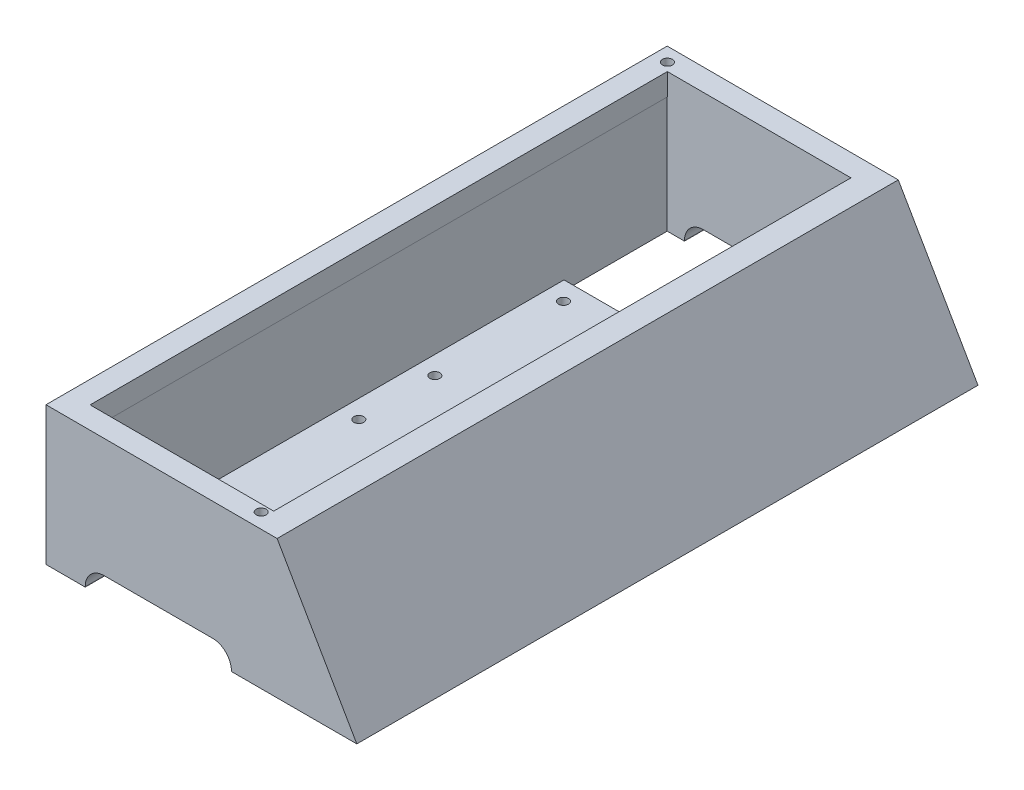
SolidWorks part; units mm, degrees
ref_plane "Alzado" through (0, 0, 0) normal (0, 0, 1) x (1, 0, 0)
ref_plane "Planta" through (0, 0, 0) normal (0, 1, 0) x (1, 0, 0)
ref_plane "Vista lateral" through (0, 0, 0) normal (1, 0, 0) x (0, 0, -1)
sketch "Sketch1" plane through (0, 0, 0) normal (0, 0, 1) x (1, 0, 0)
  line L0 (0, 0) -> (99.07, 0)
  line L1 (99.07, 0) -> (73.665, 44.0028)
  line L2 (0, 0) -> (0, 44.1)
  line L3 (0, 44.1) -> (73.665, 44.0028)
  dimension "D1" = 99.07
  dimension "D2" = 60
  dimension "D3" = 50.81
  dimension "D4" = 44.1
  dimension "D5" = 90
extrude "Boss-Extrude1" add sketch "Sketch1" along normal blind 198
shell "Shell1" thickness 7
sketch "Sketch2" plane through (68.2403, 39.3986, 0) normal (-0.866, -0.5, 0) x (0, 0, 1)
  line L0 (191, -3.5) -> (191, -45.4935) construction
  line L1 (7, -45.4935) -> (191, -45.4935)
  line L2 (7, -45.4935) -> (7, 46.3403)
  line L3 (7, 46.3403) -> (191, 46.3403)
  line L4 (191, -45.4935) -> (191, 46.3403)
  line L5 (7, -45.4935) -> (7, -2.7603) construction
  dimension "D1" = 0
  dimension "D2" = 0
extrude "Cut-Extrude1" cut sketch "Sketch2" along normal blind 10
sketch "Sketch3" plane through (0.0582, 44.0999, 0) normal (0.0013, 1, 0) x (1, -0.0013, 0)
  line L0 (7, -7) -> (90.987, -7) construction
  line L1 (7, -191) -> (58.0157, -191)
  line L2 (7, -191) -> (7, -7)
  line L3 (7, -7) -> (58.0157, -7)
  line L4 (58.0157, -191) -> (58.0157, -7)
  line L5 (7, -191) -> (90.987, -191) construction
  line L6 (7, -191) -> (7, -7) construction
  line L7 (58.0157, -7) -> (58.0157, -191) construction
  dimension "D1" = 0
  dimension "D2" = 0
  dimension "D3" = 0
  dimension "D4" = 0
extrude "Cut-Extrude3" cut sketch "Sketch3" against normal blind 10
sketch "Sketch4" plane through (0, 0, 0) normal (0, -1, 0) x (1, 0, 0)
  line L0 (7, 191) -> (7, 158.11) construction
  line L1 (7.049, 7) -> (7.049, 39.89) construction
  line L2 (90.9871, 191) -> (90.9871, 7) construction
  line L3 (7, 158.11) -> (50.2271, 158.11)
  line L4 (7, 158.11) -> (7, 39.89)
  line L5 (7, 39.89) -> (50.2271, 39.89)
  line L6 (50.2271, 158.11) -> (50.2271, 39.89)
  line L7 (7, 191) -> (90.9871, 191) construction
  line L8 (7, 7) -> (90.9871, 7) construction
  line L15 (90.9871, 81) -> (80.9871, 81)
  line L16 (90.9871, 81) -> (90.9871, 91)
  line L17 (90.9871, 91) -> (80.9871, 91)
  line L18 (80.9871, 81) -> (80.9871, 91)
  dimension "D1" = 32.89
  dimension "D2" = 32.89
  dimension "D3" = 40.76
  dimension "D4" = 32.89
  dimension "D5" = 32.89
  dimension "D8" = 10
  dimension "D10" = 0
extrude "Boss-Extrude2" add sketch "Sketch4" against normal blind 3
sketch "Sketch6" plane through (0, 3, 0) normal (0, 1, 0) x (1, 0, 0)
  circle A0 centre (12.8305, -45.8872) radius 1.585
  circle A1 centre (12.8305, -86.8872) radius 1.585
  circle A2 centre (12.8305, -111.1128) radius 1.585
  circle A3 centre (12.8305, -152.1128) radius 1.585
extrude "Cut-Extrude5" cut sketch "Sketch6" against normal blind 10
sketch "Sketch10" plane through (0, 0, 0) normal (0, -1, 0) x (1, 0, 0)
  circle A0 centre (84.0927, 85.7391) radius 1.585
extrude "Cut-Extrude8" cut sketch "Sketch10" against normal blind 5
sketch "Sketch9" plane through (0, 0, 198) normal (0, 0, 1) x (1, 0, 0)
  line L0 (0, 44.1) -> (0, 0) construction
  line L1 (12.5, 0) -> (59.0927, 0)
  line L2 (12.5, 0) -> (12.5, 6.1795)
  line L3 (12.5, 6.1795) -> (59.0927, 6.1795)
  line L4 (59.0927, 0) -> (59.0927, 6.1795)
  line L5 (71.5927, -45.1936) -> (71.5927, 0) construction
  dimension "D1" = 12.5
  dimension "D2" = 12.5
extrude "Cut-Extrude7" cut sketch "Sketch9" against normal blind 10
ref_plane "Plane1" through (0, 0, 99) normal (0, 0, -1) x (-1, 0, 0)
mirror "Mirror1" about plane through (0, 0, 99) normal (0, 0, -1) of "Cut-Extrude7"
fillet "Fillet1" radius 6 2 edges at (12.5, 6.1795, 3.5) (59.0927, 6.1795, 3.5)
fillet "Fillet2" radius 6 2 edges at (59.0927, 6.1795, 194.5) (12.5, 6.1795, 194.5)
mirror "Mirror2" about plane through (0, 0, 99) normal (0, 0, -1) of "Boss-Extrude2", "Cut-Extrude8"
sketch "Sketch11" plane through (0, 0, 0) normal (0, -1, 0) x (1, 0, 0)
  circle A0 centre (12.8305, 152.1128) radius 1.585
  circle A1 centre (12.8305, 111.1128) radius 1.585
  circle A2 centre (12.8305, 86.8872) radius 1.585
  circle A3 centre (12.8305, 45.8872) radius 1.585
extrude "Cut-Extrude9" cut sketch "Sketch11" against normal blind 5
sketch "Sketch12" plane through (0.0582, 44.0999, 0) normal (0.0013, 1, 0) x (1, -0.0013, 0)
  circle A0 centre (63.7683, -193.2457) radius 1.585
  circle A1 centre (4.417, -4.4022) radius 1.585
  point P2 (4.417, -4.4465)
  point P5 (4.417, -4.4022)
  dimension "D1" = 3.17
  dimension "D2" = 3.17
extrude "Cut-Extrude10" cut sketch "Sketch12" against normal blind 5
